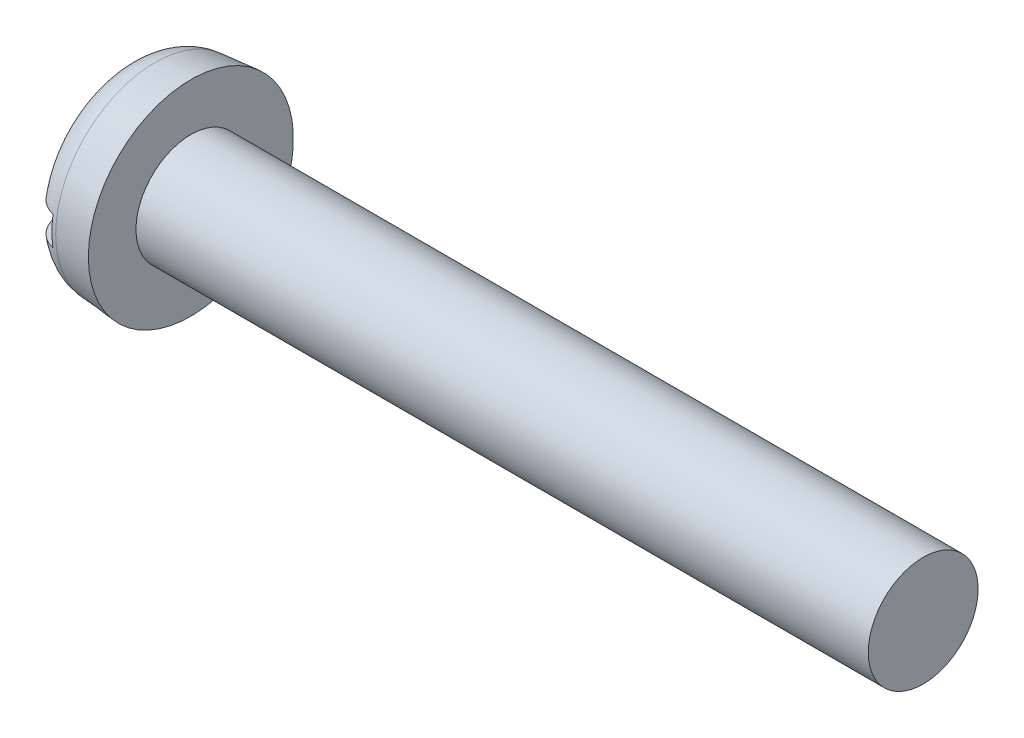
SolidWorks part; units mm, degrees
ref_plane "Plane1" through (0, 0, 0) normal (0, 0, 1) x (1, 0, 0)
ref_plane "Plane2" through (0, 0, 0) normal (0, 1, 0) x (1, 0, 0)
ref_plane "Plane3" through (0, 0, 0) normal (1, 0, 0) x (0, 0, -1)
sketch "BodySke" plane through (0, 0, 0) normal (0, 0, 1) x (1, 0, 0)
  line L0 (1.8, 1.5) -> (1.8, 2.8)
  line L1 (0, 0) -> (0, 2.6425)
  line L2 (-25.4, 0) -> (127, 0) construction
  line L3 (21.8, 0) -> (0, 0)
  line L4 (1.8, 1.5) -> (21.8, 1.5)
  line L5 (21.8, 1.5) -> (21.8, 0)
  line L6 (0, 2.6425) -> (1.8, 2.8)
  line L9 (2.3, 3.0875) -> (2.3, -6.4375) construction
  line L10 (1.8, 6.35) -> (1.8, -3.175) construction
  dimension "Head_ht" = 1.8
  dimension "Diameter" = 3
  dimension "Length" = 20
  dimension "Head_dia" = 5.6
  dimension "Advance" = 0.5
  dimension "Thread_nom" = 20
  dimension "Head_side_angle" = 5
revolve "Base-Revolve" add sketch "BodySke"
cosmetic thread "ThreadCosmetic" [suppressed]
fillet "Fillet1" [suppressed] radius 0.1
fillet "Fillet2" radius 0.9 1 edges at (0, 0, 2.6425)
sketch "Sketch2" plane through (0, 0, 0) normal (1, 0, 0) x (0, 0, -1)
  line L0 (2.8, -0.4) -> (-2.8, -0.4)
  line L1 (2.8, -0.4) -> (2.8, 0.4)
  line L2 (-2.8, 0.4) -> (2.8, 0.4)
  line L3 (-2.8, 0.4) -> (-2.8, -0.4)
  dimension "D1" = 5.6
  dimension "D2" = 2.8
  dimension "Slot_width" = 0.8
  dimension "D3" = 0.4
extrude "Slot" cut sketch "Sketch2" along normal blind 0.7
sketch "ThdSchSke" plane through (0, 0, 0) normal (0, 0, 1) x (1, 0, 0)
  line L0 (2.8, -1.2195) -> (2.6036, -1.5)
  line L1 (2.8, -1.2195) -> (2.9964, -1.5)
  line L2 (2.9964, -1.5) -> (2.9964, -1.875)
  line L3 (-3.175, 0) -> (5.1513, 0) construction
  line L5 (2.9964, -1.875) -> (2.6036, -1.875)
  line L6 (2.6036, -1.875) -> (2.6036, -1.5)
  dimension "Thread_minor" = 2.439
  dimension "Diameter" = 3
  dimension "Start" = 2.8
  dimension "SideAngle" = 55
  dimension "VeeAngle" = 70
  dimension "Overcut" = 3.75
revolve "ThreadSchematic" [suppressed] cut sketch "ThdSchSke" angle 360 about L3
pattern_linear "ThdSchPat" [suppressed]
equation "\"D1@Sketch2\" = \"Head_dia@BodySke\""
equation "\"D2@Sketch2\" = \"D1@Sketch2\" / 2"
equation "\"D3@Sketch2\" = \"Slot_width@Sketch2\" / 2"
equation "\"Thread_length@ThreadCosmetic\" = ((sgn( (\"Length@BodySke\" - \"Advance@BodySke\" * 2.0 ) - \"Thread_nom@BodySke\" )-1)*( (\"Length@BodySke\" - \"Advance@BodySke\"  * 2.0) - \"Thread_nom@BodySke\" ))/-2+ \"Thread_nom@BodySke\""
equation "\"Thread_minor@ThdSchSke\" = \"Thread_minor@ThreadCosmetic\""
equation "\"Diameter@ThdSchSke\" = \"Diameter@BodySke\""
equation "\"Overcut@ThdSchSke\" = \"Diameter@BodySke\" * 1.25"
equation "\"Start@ThdSchSke\" = \"Head_ht@BodySke\" + \"Length@BodySke\" - \"Thread_length@ThreadCosmetic\"  '---Non-countersunk---"
equation "\"Num_threads@ThdSchPat\" = int( \"Thread_length@ThreadCosmetic\" / \"Advance@BodySke\" + 0.999 )  + 1"
equation "\"Advance@ThdSchPat\" = \"Thread_length@ThreadCosmetic\" /  (\"Num_threads@ThdSchPat\" - 1) 'relax it"
